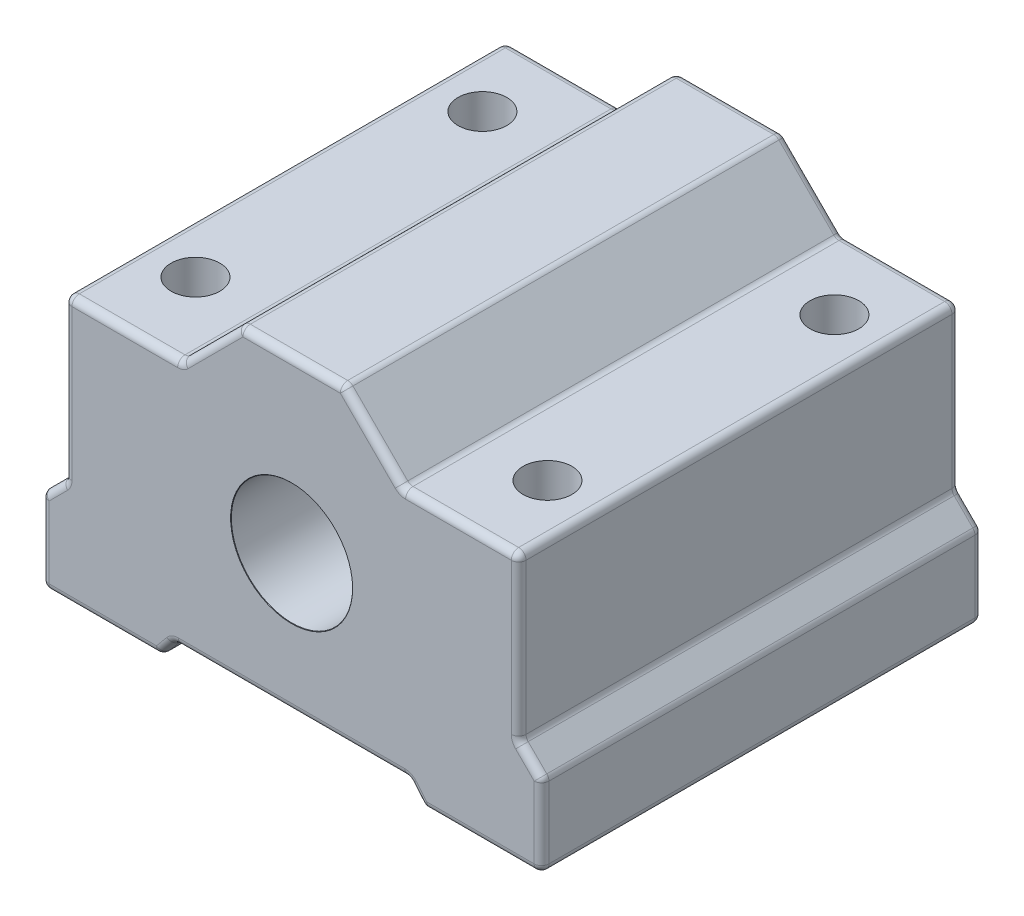
SolidWorks part; units mm, degrees
ref_plane "Front Plane" through (0, 0, 0) normal (0, 0, 1) x (1, 0, 0)
ref_plane "Top Plane" through (0, 0, 0) normal (0, 1, 0) x (1, 0, 0)
ref_plane "Right Plane" through (0, 0, 0) normal (1, 0, 0) x (0, 0, -1)
sketch "Sketch1" plane through (0, 0, 0) normal (0, 0, 1) x (1, 0, 0)
  line L0 (0, 0) -> (0, 1.5666) construction
  line L1 (-3.5, 4) -> (3.5, 4)
  line L2 (3.5, 4) -> (7.5, 0)
  line L3 (7.5, 0) -> (15.35, 0)
  line L4 (15.35, 0) -> (15.35, -10.9)
  line L5 (15.35, -10.9) -> (16.9, -12.45)
  line L6 (16.9, -12.45) -> (16.9, -18)
  line L7 (16.9, -18) -> (8.9, -18)
  line L8 (8.9, -18) -> (7.9, -16.8)
  line L9 (7.9, -16.8) -> (-7.9, -16.8)
  line L10 (-8.9, -18) -> (-7.9, -16.8)
  line L11 (-16.9, -18) -> (-8.9, -18)
  line L12 (-16.9, -12.45) -> (-16.9, -18)
  line L13 (-15.35, -10.9) -> (-16.9, -12.45)
  line L14 (-15.35, 0) -> (-15.35, -10.9)
  line L15 (-7.5, 0) -> (-15.35, 0)
  line L16 (-3.5, 4) -> (-7.5, 0)
  point P23 (0, -16.8)
  point P30 (0, 4)
  dimension "D1" = 7
  dimension "D2" = 15
  dimension "D3" = 30.7
  dimension "D4" = 33.8
  dimension "D5" = 15.8
  dimension "D6" = 8
  dimension "D7" = 18
  dimension "D8" = 20.8
  dimension "D9" = 4
  dimension "D10" = 10.9
  dimension "D11" = 4
extrude "Boss-Extrude1" add sketch "Sketch1" along normal blind 29.8
fillet "Fillet1" radius 0.5 48 edges at (3.5, 4, 14.9) (-3.5, 4, 14.9) (-7.5, 0, 14.9) (-15.35, 0, 14.9) (-15.35, -10.9, 14.9) (-16.9, -12.45, 14.9) (-16.9, -18, 14.9) (-8.9, -18, 14.9) (-7.9, -16.8, 14.9) (7.9, -16.8, 14.9) (8.9, -18, 14.9) (16.9, -18, 14.9) (16.9, -12.45, 14.9) (15.35, -10.9, 14.9) (15.35, 0, 14.9) (7.5, 0, 14.9) (11.425, 0, 29.8) (15.35, -5.45, 29.8) (16.125, -11.675, 29.8) (16.9, -15.225, 29.8) (12.9, -18, 29.8) (8.4, -17.4, 29.8) (0, -16.8, 29.8) (-8.4, -17.4, 29.8) (-12.9, -18, 29.8) (-16.9, -15.225, 29.8) (-16.125, -11.675, 29.8) (-15.35, -5.45, 29.8) (-11.425, 0, 29.8) (-5.5, 2, 29.8) (0, 4, 29.8) (5.5, 2, 29.8) (11.425, 0, 0) (15.35, -5.45, 0) (16.125, -11.675, 0) (16.9, -15.225, 0) (12.9, -18, 0) (8.4, -17.4, 0) (0, -16.8, 0) (-8.4, -17.4, 0) (-12.9, -18, 0) (-16.9, -15.225, 0) (-16.125, -11.675, 0) (-15.35, -5.45, 0) (-11.425, 0, 0) (-5.5, 2, 0) (0, 4, 0) (5.5, 2, 0)
hole_wizard "Ø8.2 (8.2) Diameter Hole1" positions "3DSketch1" profile "Sketch3" hole size "Ø8.2" standard "AS" end condition through all
sketch3d "3DSketch1"
  line L0 (7.6658, -16.8, 29.3) -> (-7.6658, -16.8, 29.3) construction
  line L1 (0, 0, 29.8) -> (0, 2.2986, 29.8) construction
  point P0 (0, -7.5135, 29.8)
  dimension "D1" = 9.3
sketch "Sketch3" plane through (0, -7.5135, 29.8) normal (1, 0, 0) x (0, -1, 0)
  line L0 (0, 0) -> (0, 29.8)
  line L1 (0, 29.8) -> (4.1, 29.8)
  line L2 (4.1, 29.8) -> (4.1, 0.025)
  line L3 (4.1, 0.025) -> (4.125, 0)
  line L5 (4.125, 0) -> (0, 0)
  line L6 (-4.1, 0.025) -> (-4.125, 0) construction
  line L11 (0, -6.35) -> (0, 107.95) construction
  dimension "Thru Hole Dia." = 8.2
  dimension "Thru Hole Depth" = 29.8
  dimension "Near C'Sink Dia." = 8.25
  dimension "Near C'Sink Angle" = 90
hole_wizard "M4 Tapped Hole1" positions "3DSketch2" profile "Sketch4" tap size "M4" standard "AS" end condition through all
sketch3d "3DSketch2"
  point P0 (11.9, -18, 24.4)
  point P2 (11.9, -18, 5)
  point P4 (-11.9, -18, 5)
  point P6 (-11.9, -18, 24.4)
  dimension "D1" = 5
  dimension "D2" = 5
  dimension "D3" = 5
  dimension "D4" = 5
  dimension "D5" = 5.4
  dimension "D6" = 5
sketch "Sketch4" plane through (11.9, -18, 24.4) normal (1, 0, 0) x (0, 0, -1)
  line L0 (0, 0) -> (0, 22)
  line L1 (0, 22) -> (1.65, 22)
  line L2 (1.65, 22) -> (1.65, 0.375)
  line L3 (1.65, 0.375) -> (2.025, 0)
  line L5 (2.025, 0) -> (0, 0)
  line L6 (-1.65, 0.375) -> (-2.025, 0) construction
  line L11 (0, -6.35) -> (0, 107.95) construction
  dimension "Thru Tap Drill Dia." = 3.3
  dimension "Thru Tap Drill Depth" = 22
  dimension "Near C'Sink Dia." = 4.05
  dimension "Near C'Sink Angle" = 90
cosmetic thread "Hole Thread1" parameters "D2"=4
cosmetic thread "Hole Thread2" parameters "D2"=4
cosmetic thread "Hole Thread3" parameters "D2"=4
cosmetic thread "Hole Thread4" parameters "D2"=4
sketch "Sketch5" plane through (0, -18, 0) normal (0, -1, 0) x (1, 0, 0)
  circle A0 centre (-11.9, 5) radius 2.025 construction
  circle A1 centre (11.9, 5) radius 2.025 construction
  circle A2 centre (11.9, 24.4) radius 2.025 construction
  circle A3 centre (-11.9, 24.4) radius 2.025 construction
  circle A4 centre (-11.9, 5) radius 2.025
  circle A5 centre (11.9, 5) radius 2.025
  circle A6 centre (11.9, 24.4) radius 2.025
  circle A7 centre (-11.9, 24.4) radius 2.025
